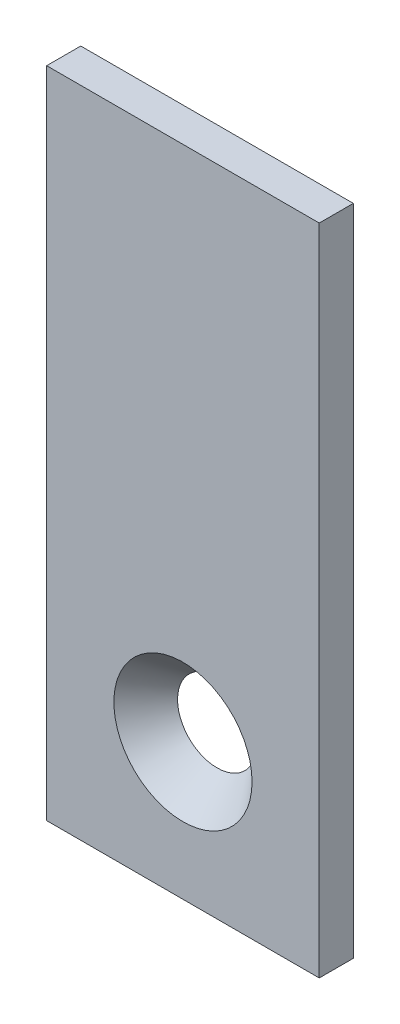
SolidWorks part; units mm, degrees
ref_plane "Front Plane" through (0, 0, 0) normal (0, 0, 1) x (1, 0, 0)
ref_plane "Top Plane" through (0, 0, 0) normal (0, 1, 0) x (1, 0, 0)
ref_plane "Right Plane" through (0, 0, 0) normal (1, 0, 0) x (0, 0, -1)
sketch "Sketch1" plane through (0, 0, 0) normal (0, 0, 1) x (1, 0, 0)
  line L1 (-12.7, -30.4644) -> (12.7, -30.4644)
  line L2 (-12.7, -30.4644) -> (-12.7, 30.4644)
  line L3 (-12.7, 30.4644) -> (12.7, 30.4644)
  line L4 (12.7, -30.4644) -> (12.7, 30.4644)
  line L5 (-12.7, -30.4644) -> (12.7, 30.4644) construction
  line L6 (-12.7, 30.4644) -> (12.7, -30.4644) construction
  point P0 (0, 0)
  dimension "D1" = 25.4
  dimension "D2" = 60.9287
extrude "Boss-Extrude1" add sketch "Sketch1" along normal mid plane 3.175
hole_wizard "CSK for 1/4 Flat Head Machine Screw1" positions "Sketch2" profile "Sketch3" countersink size "1/4" standard "ANSI Inch" end condition through all
sketch "Sketch2" plane through (0, 0, 1.5875) normal (0, 0, 1) x (1, 0, 0)
  line L0 (0, -1.7463) -> (0, 1.7463) construction
  line L1 (-12.7, -30.4644) -> (12.7, -30.4644) construction
  point P0 (0, -17.7644)
  point P3 (0, 0)
  dimension "D1" = 12.7
sketch "Sketch3" plane through (0, -17.7644, 1.5875) normal (1, 0, 0) x (0, -1, 0)
  line L0 (0, 0) -> (0, 3.175)
  line L1 (0, 3.175) -> (3.3782, 3.175)
  line L2 (3.3782, 3.175) -> (3.3782, 3.5209)
  line L3 (3.3782, 3.5209) -> (6.4389, 0)
  line L5 (6.4389, 0) -> (0, 0)
  line L6 (-3.3782, 3.5209) -> (-6.4389, 0) construction
  line L11 (0, -6.35) -> (0, 107.95) construction
  dimension "Thru Hole Dia." = 6.7564
  dimension "Thru Hole Depth" = 3.175
  dimension "Near C'Sink Dia." = 12.8778
  dimension "Near C'Sink Angle" = 82
